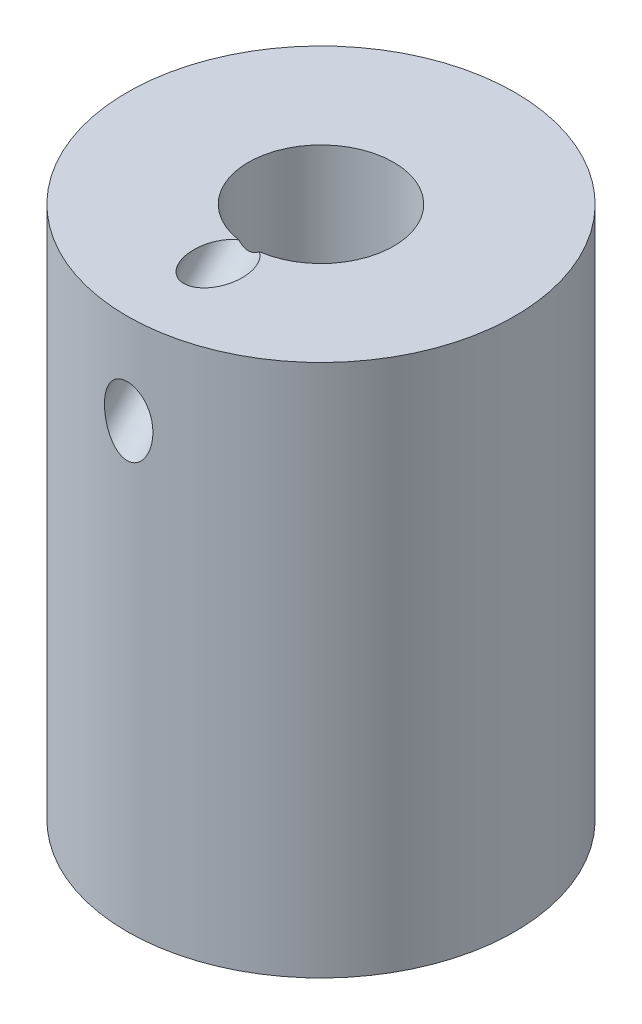
SolidWorks part; units mm, degrees
ref_plane "Front Plane" through (0, 0, 0) normal (0, 0, 1) x (1, 0, 0)
ref_plane "Top Plane" through (0, 0, 0) normal (0, 1, 0) x (1, 0, 0)
ref_plane "Right Plane" through (0, 0, 0) normal (1, 0, 0) x (0, 0, -1)
sketch "Sketch1" plane through (0, 0, 0) normal (0, 0, 1) x (1, 0, 0)
  line L0 (0, 0) -> (0, 38.1)
  line L1 (0, 38.1) -> (-8.7961, 0)
  line L2 (-8.7961, 0) -> (0, 0)
  dimension "D1" = 13
  dimension "D2" = 38.1
revolve "Revolve1" add sketch "Sketch1" angle 360 about L0
sketch "Sketch2" plane through (0, 0, 0) normal (0, -1, 0) x (1, 0, 0)
  circle A0 centre (0, 0) radius 12.7
  dimension "D1" = 25.4
extrude "Boss-Extrude1" add sketch "Sketch2" against normal blind 34.925 separate body
combine bodies "Combine1" operation type subtract main body 102 bodies to subtract 101
hole_wizard "3/8 (0.375) Diameter Hole1" positions "Sketch3" profile "Sketch4" hole size "3/8" standard "ANSI Inch" end condition through all
sketch "Sketch3" plane through (0, 34.925, 0) normal (0, 1, 0) x (1, 0, 0)
  point P0 (0, 0)
sketch "Sketch4" plane through (0, 34.925, 0) normal (1, 0, 0) x (0, 0, 1)
  line L0 (0, 0) -> (0, 34.925)
  line L1 (0, 34.925) -> (4.7625, 34.925)
  line L2 (4.7625, 34.925) -> (4.7625, 0)
  line L5 (4.7625, 0) -> (0, 0)
  line L11 (0, -6.35) -> (0, 107.95) construction
  dimension "Thru Hole Dia." = 9.525
  dimension "Thru Hole Depth" = 34.925
ref_plane "Plane1" through (0, 0, 0) normal (0, -0.7071, 0.7071) x (1, 0, 0)
hole_wizard "1/8 (0.125) Diameter Hole1" positions "Sketch5" profile "Sketch6" hole size "1/8" standard "ANSI Inch" end condition through all
sketch "Sketch5" plane through (0, 0, 0) normal (0, -0.7071, 0.7071) x (1, 0, 0)
  line L2 (0, 33.676) -> (0, 30.8696) construction
  line L3 (0, 30.8696) -> (0, 28.0633) construction
  ellipse E0 centre (0, 24.6957) end of major axis (-12.7, 24.6957) minor radius 8.9803 construction
  ellipse E1 centre (0, 24.6957) end of major axis (-12.7, 24.6957) minor radius 8.9803 construction
  ellipse E2 centre (0, 24.6957) end of major axis (4.7625, 24.6957) minor radius 3.3676 construction
  ellipse E3 centre (0, 24.6957) end of major axis (4.7625, 24.6957) minor radius 3.3676 construction
  point P0 (0, 29.4665)
  point P36 (0, 0)
sketch "Sketch6" plane through (0, 20.8359, 20.8359) normal (1, 0, 0) x (0, -0.7071, -0.7071)
  line L0 (0, 0) -> (0, 33.676)
  line L1 (0, 33.676) -> (1.5875, 33.676)
  line L2 (1.5875, 33.676) -> (1.5875, 0)
  line L5 (1.5875, 0) -> (0, 0)
  line L11 (0, -6.35) -> (0, 107.95) construction
  dimension "Thru Hole Dia." = 3.175
  dimension "Thru Hole Depth" = 33.676
